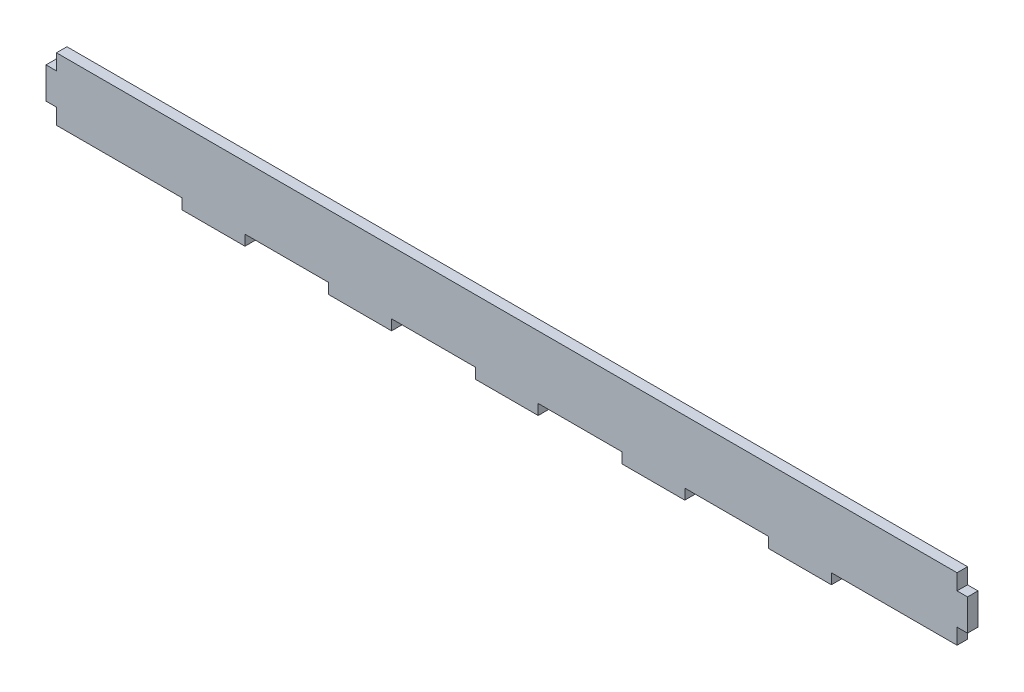
SolidWorks part; units mm, degrees
ref_plane "Front Plane" through (0, 0, 0) normal (0, 0, 1) x (1, 0, 0)
ref_plane "Top Plane" through (0, 0, 0) normal (0, 1, 0) x (1, 0, 0)
ref_plane "Right Plane" through (0, 0, 0) normal (1, 0, 0) x (0, 0, -1)
sketch "Sketch1" plane through (0, 0, 0) normal (0, 0, 1) x (1, 0, 0)
  line L0 (225, -390) -> (225, -352.4381) construction
  line L2 (440.0003, -430) -> (440.0003, -422.5)
  line L4 (9.9997, -430) -> (9.9997, -422.5)
  line L5 (210, -430) -> (170, -430)
  line L7 (240, -430) -> (240, -435)
  line L8 (240, -435) -> (210, -435)
  line L9 (210, -430) -> (210, -435)
  line L10 (225, -430) -> (210, -435) construction
  line L11 (240, -435) -> (225, -430) construction
  line L12 (170, -430) -> (170, -435)
  line L13 (170, -435) -> (140, -435)
  line L14 (140, -430) -> (140, -435)
  line L15 (100, -430) -> (100, -435)
  line L16 (100, -435) -> (70, -435)
  line L17 (70, -430) -> (70, -435)
  line L18 (240, -430) -> (240, -435)
  line L19 (240, -435) -> (210, -435)
  line L20 (210, -430) -> (210, -435)
  line L21 (170, -430) -> (170, -435)
  line L22 (170, -435) -> (140, -435)
  line L23 (140, -430) -> (140, -435)
  line L24 (310, -430) -> (310, -435)
  line L25 (310, -435) -> (280, -435)
  line L26 (280, -430) -> (280, -435)
  line L27 (240, -430) -> (240, -435)
  line L28 (240, -435) -> (210, -435)
  line L29 (210, -430) -> (210, -435)
  line L30 (310, -430) -> (310, -435)
  line L31 (310, -435) -> (280, -435)
  line L32 (280, -430) -> (280, -435)
  line L33 (380, -430) -> (380, -435)
  line L34 (380, -435) -> (350, -435)
  line L35 (350, -430) -> (350, -435)
  line L36 (280, -430) -> (240, -430)
  line L37 (350, -430) -> (310, -430)
  line L38 (140, -430) -> (100, -430)
  line L39 (445, -420) -> (445, -428.3396) construction
  line L40 (440.0003, -407.5) -> (440.0003, -400)
  line L41 (440.0003, -422.5) -> (445, -422.5)
  line L43 (440.0003, -407.5) -> (445, -407.5)
  line L44 (445, -422.5) -> (445, -407.5)
  line L47 (440.0003, -430) -> (380, -430)
  line L48 (70, -430) -> (9.9997, -430)
  line L49 (5, -422.5) -> (5, -407.5)
  line L50 (9.9997, -407.5) -> (5, -407.5)
  line L51 (9.9997, -422.5) -> (5, -422.5)
  line L52 (9.9997, -407.5) -> (9.9997, -400)
  line L53 (9.9997, -400) -> (440.0003, -400)
  point P7 (225, -430)
  point P9 (440.0003, -410)
  point P38 (0, 0)
  point P49 (9.9997, -410)
  point P51 (440.0003, -421.2344)
  point P52 (0, 0)
  dimension "D1" = 30
  dimension "D2" = 7.5
  dimension "D3" = 30
  dimension "D7" = 15
  dimension "D8" = 4.9997
  dimension "D5" = 3
  dimension "D6" = 3
extrude "Boss-Extrude1" add sketch "Sketch1" against normal blind 5
